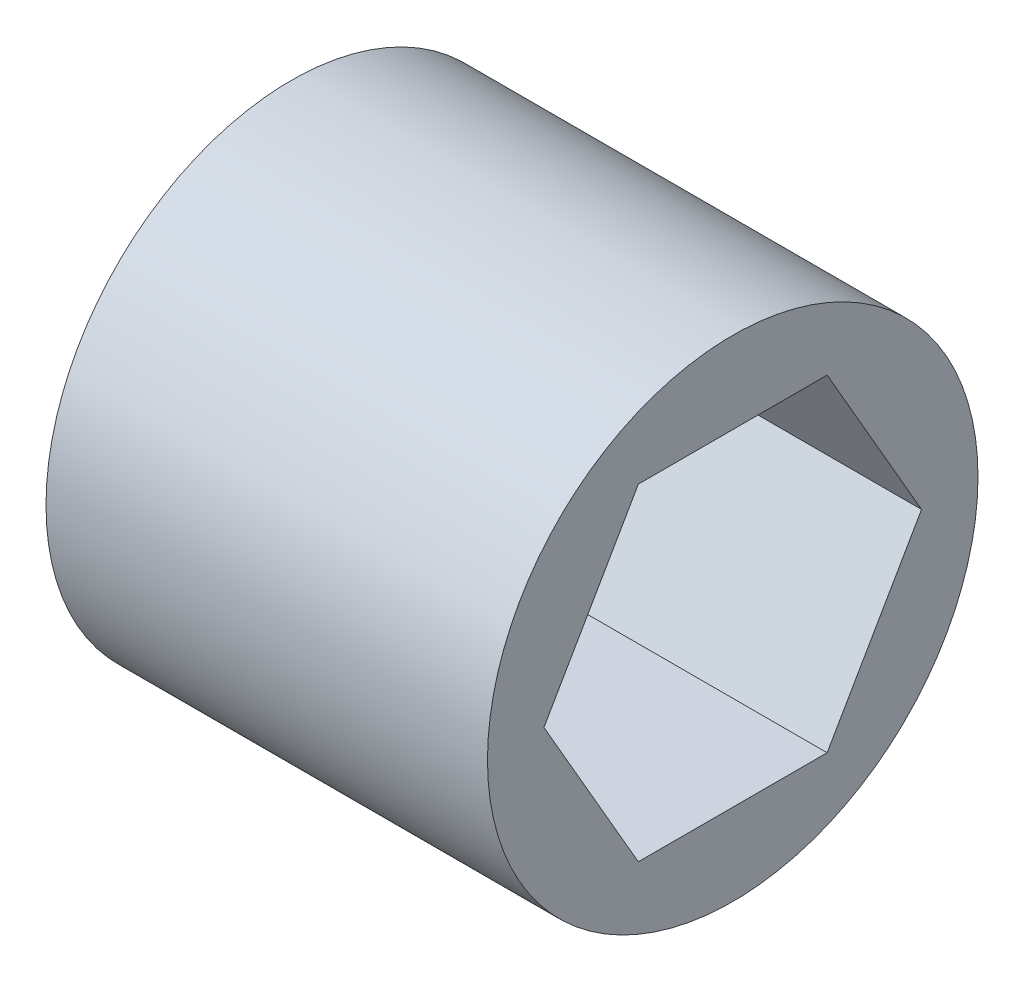
SolidWorks part; units mm, degrees
material "PET"
ref_plane "Front" through (0, 0, 0) normal (0, 0, 1) x (1, 0, 0)
ref_plane "Top" through (0, 0, 0) normal (0, 1, 0) x (1, 0, 0)
ref_plane "Right" through (0, 0, 0) normal (1, 0, 0) x (0, 0, -1)
sketch "Sketch1" plane through (0, 0, 0) normal (1, 0, 0) x (0, 0, -1)
  line L1 (7.3323, 0) -> (3.6662, 6.35)
  line L2 (3.6662, 6.35) -> (-3.6662, 6.35)
  line L3 (-3.6662, 6.35) -> (-7.3323, 0)
  line L4 (-7.3323, 0) -> (-3.6662, -6.35)
  line L5 (-3.6662, -6.35) -> (3.6662, -6.35)
  line L6 (3.6662, -6.35) -> (7.3323, 0)
  circle A0 centre (0, 0) radius 6.35 construction
  circle A1 centre (0, 0) radius 9.525
  dimension "D2" = 19.05
  dimension "D1" = 12.7
extrude "Boss-Extrude1" add sketch "Sketch1" along normal blind 17.145
